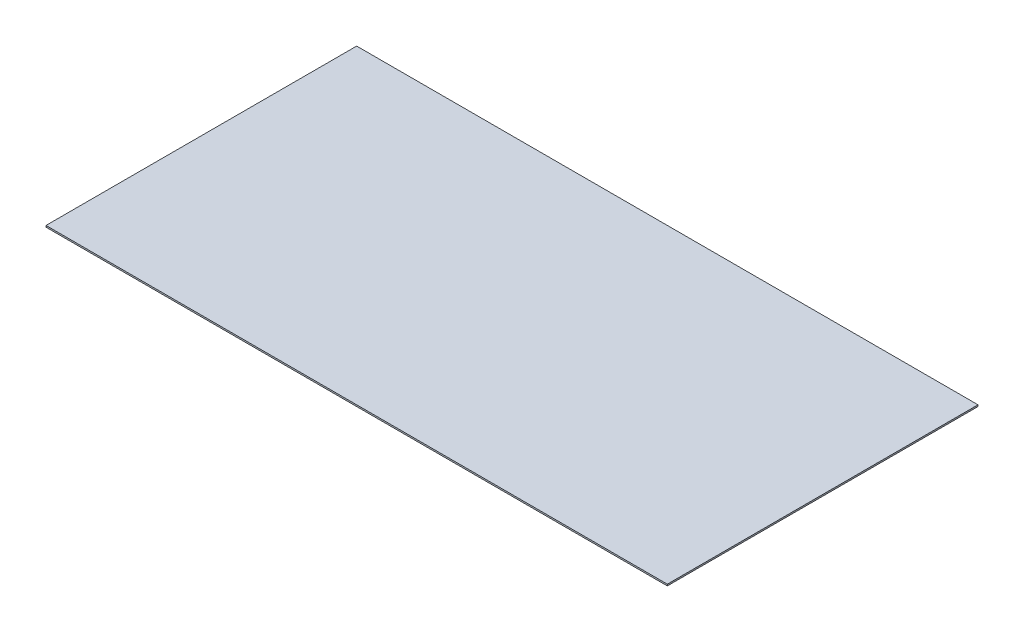
SolidWorks part; units mm, degrees
ref_plane "Front Plane" through (0, 0, 0) normal (0, 0, 1) x (1, 0, 0)
ref_plane "Top Plane" through (0, 0, 0) normal (0, 1, 0) x (1, 0, 0)
ref_plane "Right Plane" through (0, 0, 0) normal (1, 0, 0) x (0, 0, -1)
sketch "Sketch1" plane through (0, 0, 0) normal (0, 1, 0) x (1, 0, 0)
  line L1 (-600, 300) -> (600, 300)
  line L2 (-600, 300) -> (-600, -300)
  line L3 (-600, -300) -> (600, -300)
  line L4 (600, 300) -> (600, -300)
  line L5 (-600, 300) -> (600, -300) construction
  line L6 (-600, -300) -> (600, 300) construction
  point P0 (0, 0)
extrude "Boss-Extrude1" add sketch "Sketch1" along normal blind 3
